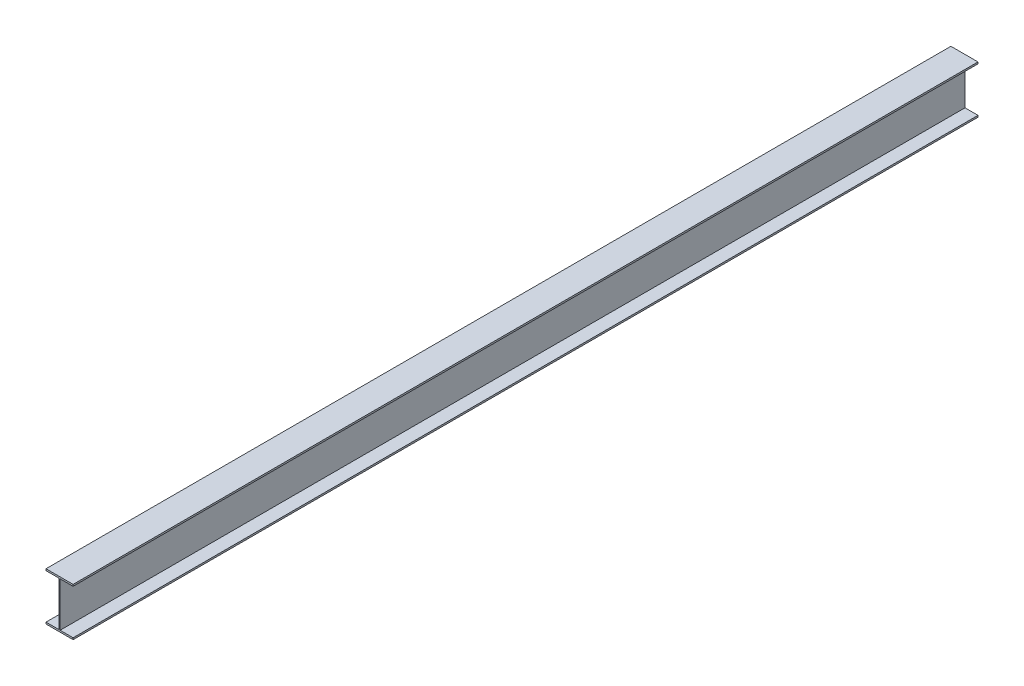
SolidWorks part; units mm, degrees
ref_plane "Front Plane" through (0, 0, 0) normal (0, 0, 1) x (1, 0, 0)
ref_plane "Top Plane" through (0, 0, 0) normal (0, 1, 0) x (1, 0, 0)
ref_plane "Right Plane" through (0, 0, 0) normal (1, 0, 0) x (0, 0, -1)
sketch "Sketch2" plane through (0, 0, 0) normal (0, 0, 1) x (1, 0, 0)
  line L0 (-73.025, 129.159) -> (-73.025, 120.015)
  line L1 (-73.025, -129.159) -> (73.025, -129.159)
  line L2 (-73.025, -129.159) -> (-73.025, -120.015)
  line L3 (-73.025, 129.159) -> (73.025, 129.159)
  line L4 (73.025, -129.159) -> (73.025, -120.015)
  line L5 (-73.025, -129.159) -> (73.025, 129.159) construction
  line L6 (-73.025, 129.159) -> (73.025, -129.159) construction
  line L7 (-3.048, 0) -> (0, 0)
  line L8 (-73.025, 120.015) -> (-3.048, 120.015)
  line L9 (73.025, 120.015) -> (3.048, 120.015)
  line L10 (-3.048, 120.015) -> (-3.048, -120.015)
  line L11 (3.048, 120.015) -> (3.048, -120.015)
  line L12 (73.025, -120.015) -> (3.048, -120.015)
  line L13 (-73.025, -120.015) -> (-3.048, -120.015)
  line L14 (73.025, 120.015) -> (73.025, 129.159)
  line L15 (-73.025, 120.015) -> (-73.025, 129.159)
  point P0 (0, 0)
  point P13 (3.048, 0)
  point P18 (-3.048, 0)
  dimension "D1" = 258.318
  dimension "D2" = 146.05
  dimension "D3" = 9.144
  dimension "D4" = 6.096
  dimension "D5" = 69.977
extrude "Boss-Extrude1" add sketch "Sketch2" along normal blind 4876.8
